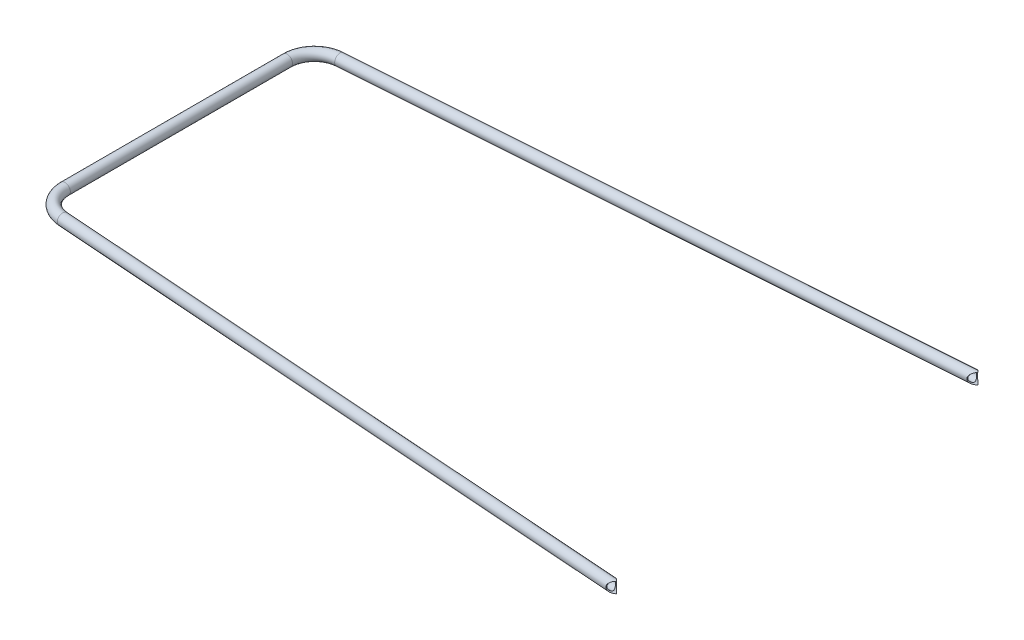
SolidWorks part; units mm, degrees
material "AISI 304"
ref_plane "Plano frontal" through (0, 0, 0) normal (0, 0, 1) x (1, 0, 0)
ref_plane "Plano superior" through (0, 0, 0) normal (0, 1, 0) x (1, 0, 0)
ref_plane "Plano direito" through (0, 0, 0) normal (1, 0, 0) x (0, 0, -1)
sketch "Esboço1" plane through (0, 0, 0) normal (0, 1, 0) x (1, 0, 0)
  line L0 (0, 162.7552) -> (0, -162.7552)
  line L1 (0, 0) -> (910, 0) construction
  line L2 (910, 265) -> (910, -265) construction
  line L3 (37.1501, 202.6536) -> (910, 265)
  line L4 (37.1501, -202.6536) -> (910, -265)
  arc A0 (0, -162.7552) -> (37.1501, -202.6536) centre (40, -162.7552) ccw
  arc A1 (0, 162.7552) -> (37.1501, 202.6536) centre (40, 162.7552) cw
  point P9 (0, -200)
  point P12 (0, 200)
  dimension "D4" = 40
  dimension "D1" = 400
  dimension "D2" = 910
  dimension "D3" = 530
other "Pipe - configured 21.3 X 2.3(1)"
ref_plane "Plano1" through (37.1501, 0, 202.6536) normal (0.9975, 0, 0.0712) x (0.0712, 0, -0.9975)
sketch "Sketch1" plane through (37.1501, 0, 202.6536) normal (0.9975, 0, 0.0712) x (0.0712, 0, -0.9975)
  circle A0 centre (0, 0) radius 6.4375
  circle A1 centre (0, 0) radius 7.9375
  point P3 (0, 0)
  dimension "D1" = 15.875
  dimension "D2" = 1.5
ref_plane "Plano3" through (0, 0, 0) normal (0, 0, 1) x (1, 0, 0)
sketch "Esboço2" plane through (0, 0, 0) normal (0, 0, 1) x (1, 0, 0)
  line L0 (37.1501, 0) -> (910, 0) construction
  circle A0 centre (910, 0) radius 7.9375
extrude "Corte-extrusão1" cut sketch "Esboço2" against normal through all both and the other way through all
